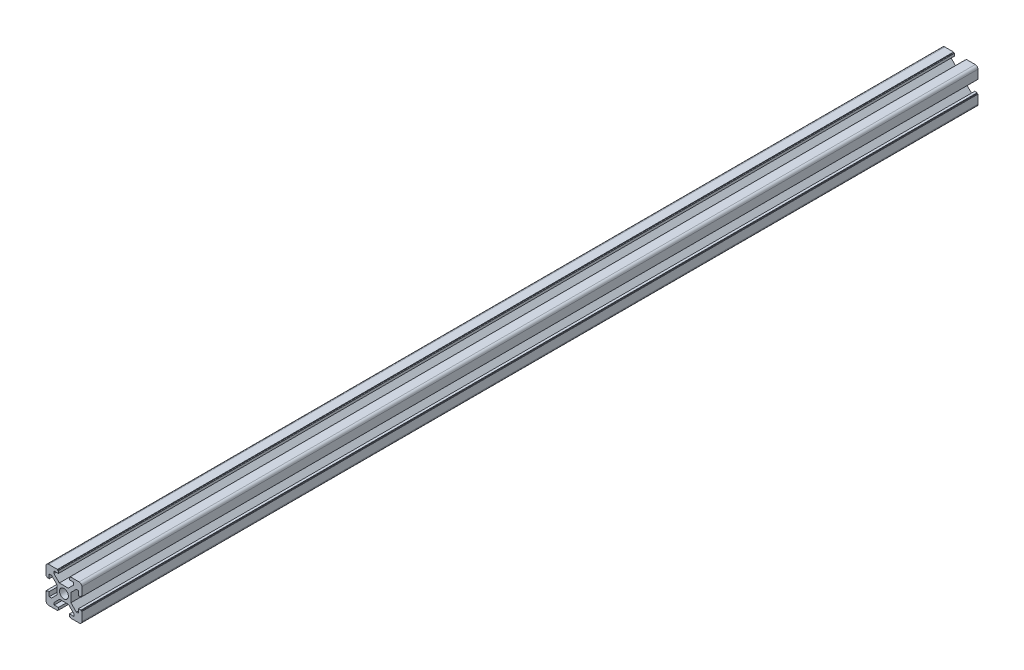
SolidWorks part; units mm, degrees
ref_plane "Front Plane" through (0, 0, 0) normal (0, 0, 1) x (1, 0, 0)
ref_plane "Top Plane" through (0, 0, 0) normal (0, 1, 0) x (1, 0, 0)
ref_plane "Right Plane" through (0, 0, 0) normal (1, 0, 0) x (0, 0, -1)
ref_plane "Plane1" through (0, 0, 0) normal (0, 0, -1) x (-1, 0, 0)
sketch "Sketch1" plane through (0, 0, 0) normal (0, 0, -1) x (-1, 0, 0)
  line L0 (-31.2291, 24.3895) -> (-31.2291, 19.5741)
  line L1 (-31.2291, 19.5741) -> (-30.8015, 19.5741)
  line L2 (-30.8015, 19.5741) -> (-30.8015, 19.0554)
  line L3 (-30.8015, 19.0554) -> (-29.4291, 19.0554)
  line L4 (-29.4291, 19.0554) -> (-29.4291, 21.5235)
  line L5 (-29.4291, 21.5235) -> (-28.1416, 21.5235)
  line L6 (-28.1416, 21.5235) -> (-25.1291, 18.511)
  line L7 (-25.1291, 18.511) -> (-25.1291, 13.533)
  line L8 (-25.1291, 13.533) -> (-28.1416, 10.5205)
  line L9 (-28.1416, 10.5205) -> (-29.4291, 10.5205)
  line L10 (-29.4291, 10.5205) -> (-29.4291, 12.8554)
  line L11 (-29.4291, 12.8554) -> (-30.8015, 12.8554)
  line L12 (-30.8015, 12.8554) -> (-30.8015, 12.3507)
  line L13 (-30.8015, 12.3507) -> (-31.2291, 12.3507)
  line L14 (-31.2291, 12.3507) -> (-31.2291, 7.5212)
  line L15 (-29.7291, 6.0212) -> (-24.8478, 6.0212)
  line L16 (-24.8478, 6.0212) -> (-24.8478, 6.383)
  line L17 (-24.8478, 6.383) -> (-24.3291, 6.383)
  line L18 (-24.3291, 6.383) -> (-24.3291, 7.7554)
  line L19 (-24.3291, 7.7554) -> (-26.7973, 7.7554)
  line L20 (-26.7973, 7.7554) -> (-26.7973, 9.0429)
  line L21 (-26.7973, 9.0429) -> (-23.7848, 12.0554)
  line L22 (-23.7848, 12.0554) -> (-18.8067, 12.0554)
  line L23 (-18.8067, 12.0554) -> (-15.7942, 9.0429)
  line L24 (-15.7942, 9.0429) -> (-15.7942, 7.7554)
  line L25 (-15.7942, 7.7554) -> (-18.1291, 7.7554)
  line L26 (-18.1291, 7.7554) -> (-18.1291, 6.383)
  line L27 (-18.1291, 6.383) -> (-17.6244, 6.383)
  line L28 (-17.6244, 6.383) -> (-17.6244, 6.0212)
  line L29 (-17.6244, 6.0212) -> (-12.7291, 6.0212)
  line L30 (-11.2291, 7.5212) -> (-11.2291, 12.3367)
  line L31 (-11.2291, 12.3367) -> (-11.6567, 12.3367)
  line L32 (-11.6567, 12.3367) -> (-11.6567, 12.8554)
  line L33 (-11.6567, 12.8554) -> (-13.0291, 12.8554)
  line L34 (-13.0291, 12.8554) -> (-13.0291, 10.3872)
  line L35 (-13.0291, 10.3872) -> (-14.3166, 10.3872)
  line L36 (-14.3166, 10.3872) -> (-17.3291, 13.3997)
  line L37 (-17.3291, 13.3997) -> (-17.3291, 18.3778)
  line L38 (-17.3291, 18.3778) -> (-14.3166, 21.3903)
  line L39 (-14.3166, 21.3903) -> (-13.0291, 21.3903)
  line L40 (-13.0291, 21.3903) -> (-13.0291, 19.0554)
  line L41 (-13.0291, 19.0554) -> (-11.6567, 19.0554)
  line L42 (-11.6567, 19.0554) -> (-11.6567, 19.56)
  line L43 (-11.6567, 19.56) -> (-11.2291, 19.56)
  line L44 (-11.2291, 19.56) -> (-11.2291, 24.3895)
  line L45 (-12.7291, 25.8895) -> (-17.6104, 25.8895)
  line L46 (-17.6104, 25.8895) -> (-17.6104, 25.5277)
  line L47 (-17.6104, 25.5277) -> (-18.1291, 25.5277)
  line L48 (-18.1291, 25.5277) -> (-18.1291, 24.1554)
  line L49 (-18.1291, 24.1554) -> (-15.661, 24.1554)
  line L50 (-15.661, 24.1554) -> (-15.661, 22.8679)
  line L51 (-15.661, 22.8679) -> (-18.6734, 19.8554)
  line L52 (-18.6734, 19.8554) -> (-23.6515, 19.8554)
  line L53 (-23.6515, 19.8554) -> (-26.664, 22.8679)
  line L54 (-26.664, 22.8679) -> (-26.664, 24.1554)
  line L55 (-26.664, 24.1554) -> (-24.3291, 24.1554)
  line L56 (-24.3291, 24.1554) -> (-24.3291, 25.5277)
  line L57 (-24.3291, 25.5277) -> (-24.8338, 25.5277)
  line L58 (-24.8338, 25.5277) -> (-24.8338, 25.8895)
  line L59 (-24.8338, 25.8895) -> (-29.7291, 25.8895)
  circle A0 centre (-21.2291, 15.9554) radius 2.5
  arc A1 (-31.2291, 7.5212) -> (-29.7291, 6.0212) centre (-29.7291, 7.5212) ccw
  arc A2 (-12.7291, 6.0212) -> (-11.2291, 7.5212) centre (-12.7291, 7.5212) ccw
  arc A3 (-11.2291, 24.3895) -> (-12.7291, 25.8895) centre (-12.7291, 24.3895) ccw
  arc A4 (-29.7291, 25.8895) -> (-31.2291, 24.3895) centre (-29.7291, 24.3895) ccw
extrude "Boss-Extrude1" add sketch "Sketch1" against normal blind 500
